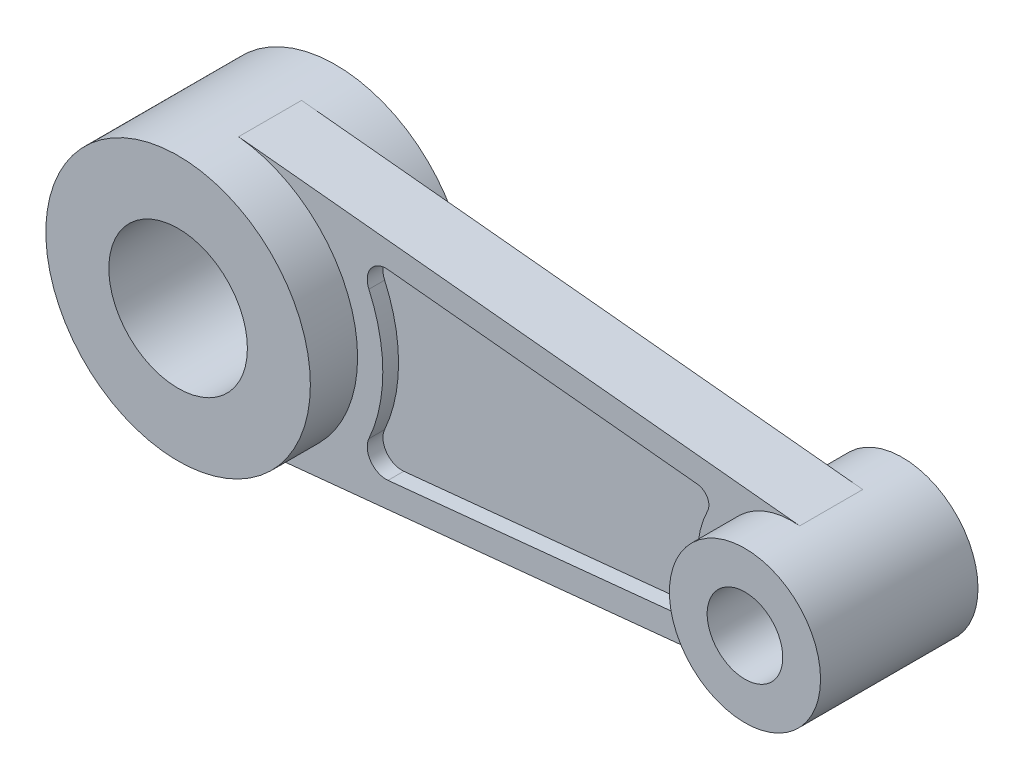
SolidWorks part; units mm, degrees
ref_plane "Front Plane" through (0, 0, 0) normal (0, 0, 1) x (1, 0, 0)
ref_plane "Top Plane" through (0, 0, 0) normal (0, 1, 0) x (1, 0, 0)
ref_plane "Right Plane" through (0, 0, 0) normal (1, 0, 0) x (0, 0, -1)
sketch "Sketch6" plane through (0, 0, 0) normal (0, 0, 1) x (1, 0, 0)
  line L1 (53.34, 530.7263) -> (2316.48, 303.2722)
  line L2 (53.34, -530.7263) -> (2316.48, -303.2722)
  arc A0 (53.34, -530.7263) -> (53.34, 530.7263) centre (0, 0) ccw
  arc A1 (2316.48, 303.2722) -> (2316.48, -303.2722) centre (2286, 0) ccw
  dimension "D1" = 533.4
  dimension "D2" = 304.8
  dimension "D3" = 53.34
extrude "Boss-Extrude4" add sketch "Sketch6" along normal mid plane 254
ref_plane "Plane1" through (53.34, -530.7263, -127) normal (-0.995, -0.1, 0) x (0, 0, 1)
sketch "Sketch12" plane through (0, 0, 0) normal (0, 0, 1) x (1, 0, 0)
  circle A0 centre (0, 0) radius 533.4
  circle A1 centre (2286, 0) radius 304.8
extrude "Boss-Extrude5" add sketch "Sketch12" along normal mid plane 635
sketch "Sketch13" plane through (0, 0, 0) normal (0, 0, 1) x (1, 0, 0)
  circle A0 centre (0, 0) radius 279.4
  circle A1 centre (2286, 0) radius 152.4
  dimension "D1" = 558.8
  dimension "D2" = 304.8
extrude "Cut-Extrude3" cut sketch "Sketch13" against normal through all both and the other way through all
sketch "Sketch14" plane through (0, 0, 127) normal (0, 0, 1) x (1, 0, 0)
  line L4 (2306.32, 202.1814) -> (43.18, 429.6356)
  line L5 (1904.3334, 242.5826) -> (656.0099, 368.0438)
  line L7 (43.18, -429.6356) -> (2306.32, -202.1814)
  line L8 (656.0099, -368.0438) -> (1904.3334, -242.5826)
  arc A0 (578.9196, -260.9159) -> (578.9196, 260.9159) centre (0, 0) ccw
  arc A1 (1944.753, 169.4446) -> (1944.753, -169.4446) centre (2286, 0) ccw
  arc A2 (656.0099, 368.0438) -> (578.9196, 260.9159) centre (648.3899, 292.2258) ccw
  arc A3 (578.9196, -260.9159) -> (656.0099, -368.0438) centre (648.3899, -292.2258) ccw
  arc A4 (1944.753, 169.4446) -> (1904.3334, 242.5826) centre (1899.2534, 192.0373) ccw
  arc A5 (1904.3334, -242.5826) -> (1944.753, -169.4446) centre (1899.2534, -192.0373) ccw
  dimension "D3" = 152.4
  dimension "D4" = 152.4
  dimension "D5" = 101.6
  dimension "D6" = 101.6
  dimension "D1" = 101.6
  dimension "D2" = 101.6
extrude "Cut-Extrude4" cut sketch "Sketch14" against normal blind 63.5
sketch "Sketch15" plane through (0, 0, -127) normal (0, 0, -1) x (-1, 0, 0)
  line L4 (-2306.32, 202.1814) -> (-43.18, 429.6356)
  line L5 (-1904.3334, 242.5826) -> (-656.0099, 368.0438)
  line L7 (-43.18, -429.6356) -> (-2306.32, -202.1814)
  line L8 (-656.0099, -368.0438) -> (-1904.3334, -242.5826)
  arc A2 (-1944.753, -169.4446) -> (-1944.753, 169.4446) centre (-2286, 0) ccw
  arc A3 (-578.9196, 260.9159) -> (-578.9196, -260.9159) centre (0, 0) ccw
  arc A4 (-1904.3334, 242.5826) -> (-1944.753, 169.4446) centre (-1899.2534, 192.0373) ccw
  arc A5 (-1944.753, -169.4446) -> (-1904.3334, -242.5826) centre (-1899.2534, -192.0373) ccw
  arc A6 (-578.9196, 260.9159) -> (-656.0099, 368.0438) centre (-648.3899, 292.2258) ccw
  arc A7 (-656.0099, -368.0438) -> (-578.9196, -260.9159) centre (-648.3899, -292.2258) ccw
  dimension "D3" = 101.6
  dimension "D4" = 101.6
  dimension "D5" = 152.4
  dimension "D6" = 152.4
  dimension "D1" = 101.6
  dimension "D2" = 101.6
extrude "Cut-Extrude5" cut sketch "Sketch15" against normal blind 63.5
